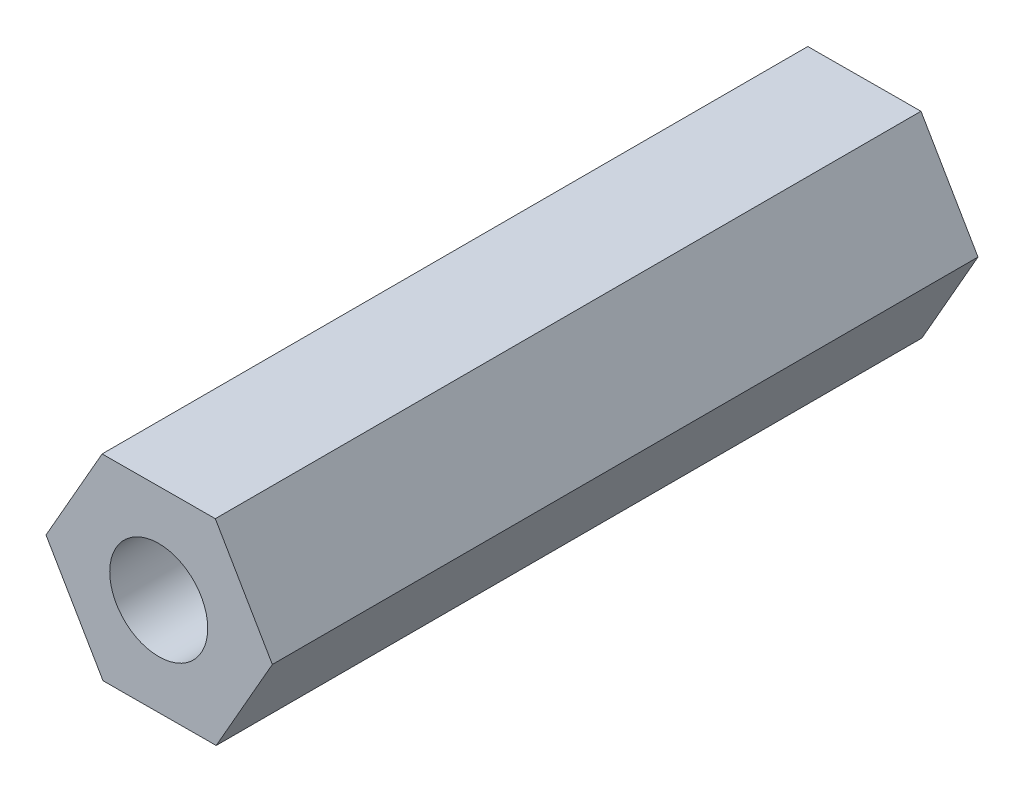
SolidWorks part; units mm, degrees
ref_plane "前视基准面" through (0, 0, 0) normal (0, 0, 1) x (1, 0, 0)
ref_plane "上视基准面" through (0, 0, 0) normal (0, 1, 0) x (1, 0, 0)
ref_plane "右视基准面" through (0, 0, 0) normal (1, 0, 0) x (0, 0, -1)
sketch "草图1" plane through (0, 0, 0) normal (0, 0, 1) x (1, 0, 0)
  line L1 (-66.8574, 15.1689) -> (-65.4252, 17.6753)
  line L2 (-65.4252, 17.6753) -> (-66.8797, 20.1688)
  line L3 (-66.8797, 20.1688) -> (-69.7665, 20.1559)
  line L4 (-69.7665, 20.1559) -> (-71.1986, 17.6495)
  line L5 (-71.1986, 17.6495) -> (-69.7441, 15.156)
  line L6 (-69.7441, 15.156) -> (-66.8574, 15.1689)
  circle A0 centre (-68.3119, 17.6624) radius 2.5 construction
  dimension "D1" = 5
extrude "凸台-拉伸1" add sketch "草图1" along normal blind 18
sketch "草图2" plane through (0, 0, 0) normal (0, 0, -1) x (-1, 0, 0)
  circle A0 centre (68.3231, 17.6495) radius 1.25
  dimension "D1" = 2.5
extrude "切除-拉伸1" cut sketch "草图2" against normal blind 25
